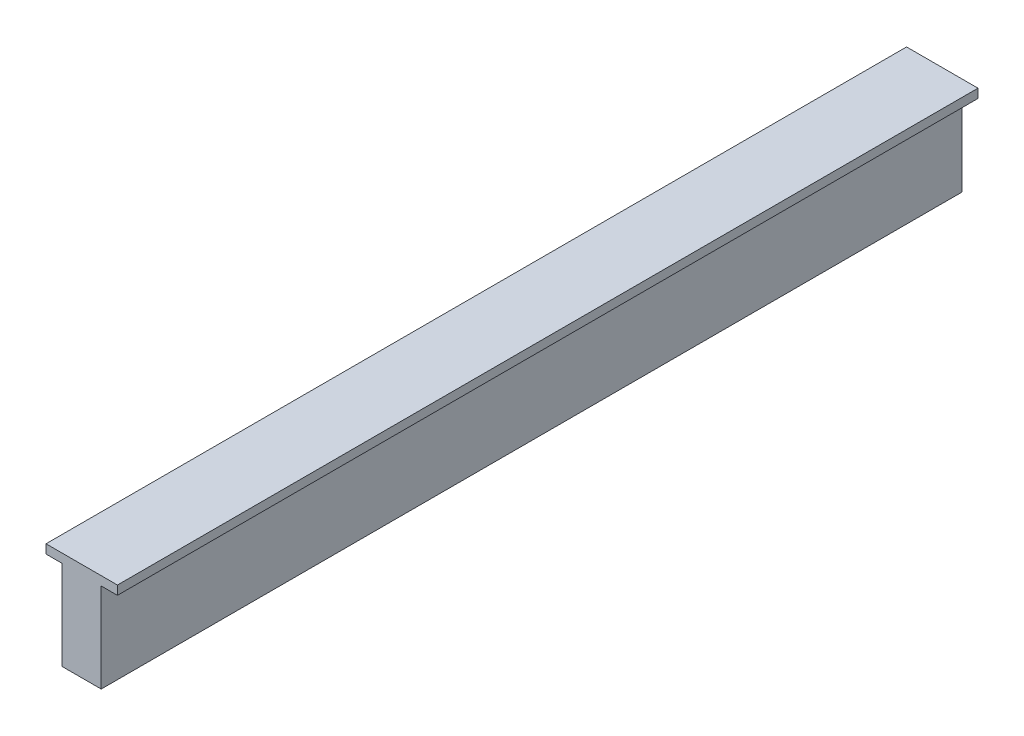
SolidWorks part; units mm, degrees
material "Choose your Material"
ref_plane "Front Plane" through (0, 0, 0) normal (0, 0, 1) x (1, 0, 0)
ref_plane "Top Plane" through (0, 0, 0) normal (0, 1, 0) x (1, 0, 0)
ref_plane "Right Plane" through (0, 0, 0) normal (1, 0, 0) x (0, 0, -1)
sketch "Sketch1" plane through (0, 0, 0) normal (0, 0, 1) x (1, 0, 0)
  line L0 (-22, 0) -> (22, 0)
  line L1 (22, 0) -> (22, -5.5)
  line L2 (22, -5.5) -> (12, -5.5)
  line L3 (12, -5.5) -> (12, -60.5)
  line L4 (12, -60.5) -> (-12, -60.5)
  line L5 (-12, -60.5) -> (-12, -5.5)
  line L6 (-12, -5.5) -> (-22, -5.5)
  line L7 (-22, -5.5) -> (-22, 0)
  point P3 (0, 0)
  dimension "D1" = 5.5
  dimension "D2" = 44
  dimension "D3" = 55
  dimension "D4" = 10
extrude "Boss-Extrude1" add sketch "Sketch1" along normal mid plane 530
